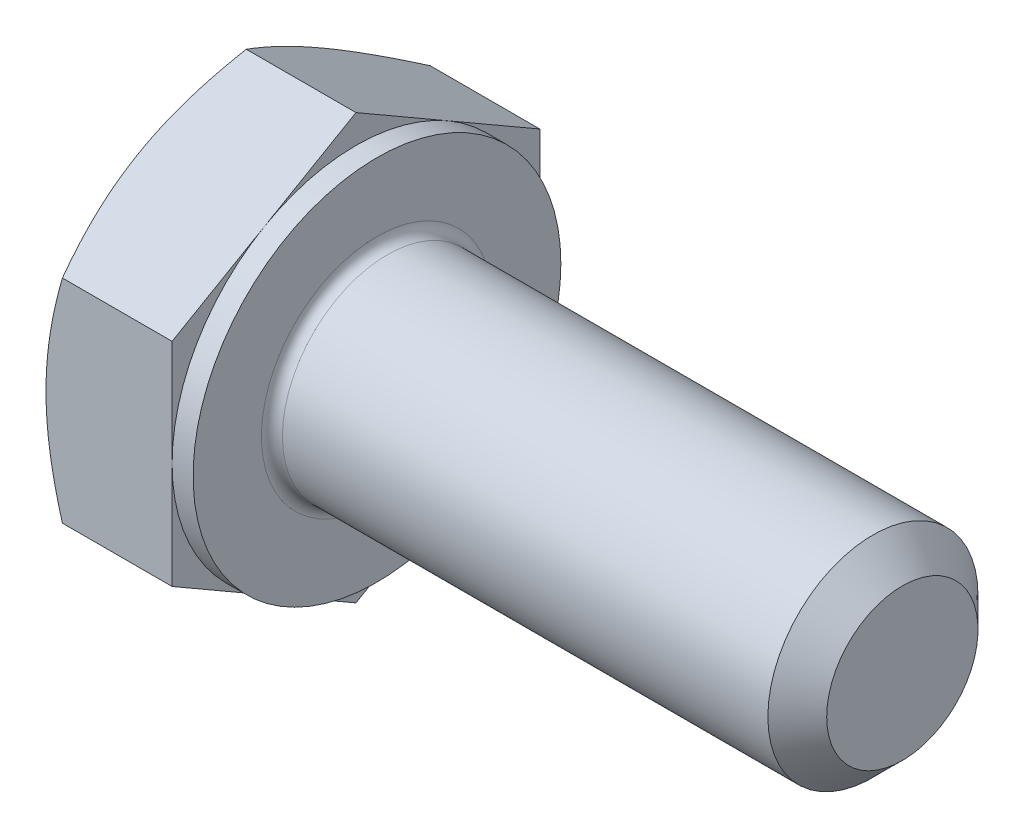
SolidWorks part; units mm, degrees
extrude "基体-拉伸" add sketch "草图1" along normal blind 2.8
sketch "草图1" plane through (0, 0, 0) normal (1, 0, 0) x (0, 0, -1)
  line L0 (3.5, 2.0207) -> (3.5, -2.0207)
  line L1 (-3.5, 2.0207) -> (-3.5, -2.0207)
  line L2 (3.5, -2.0207) -> (0, -4.0415)
  line L3 (0, -4.0415) -> (-3.5, -2.0207)
  line L4 (3.5, 2.0207) -> (0, 4.0415)
  line L5 (0, 4.0415) -> (-3.5, 2.0207)
  dimension "s" = 7
  dimension "D2" = 120
  dimension "D3" = 3.5
  dimension "D4" = 3.5
  dimension "D5" = 3.5
revolve "切除-旋转1" cut sketch "草图3" angle 360 about L6
sketch "草图3" plane through (0, 0, 0) normal (0, 0, 1) x (1, 0, 0)
  line L0 (0, 3.5) -> (3.1994, 9.0415)
  line L1 (0, 4.0415) -> (0, 2.0207) construction
  line L2 (3.1994, 9.0415) -> (3.1994, 14.0415)
  line L3 (3.1994, 14.0415) -> (-10, 14.0415)
  line L4 (-10, 14.0415) -> (-10, 3.5)
  line L5 (-10, 3.5) -> (0, 3.5)
  line L6 (0, 0) -> (99.06, 0) construction
  line L7 (2.8, 4.0415) -> (0, 4.0415) construction
  dimension "D1" = 3.5
  dimension "D2" = 5
  dimension "D3" = 10
  dimension "D4" = 5
  dimension "Head_ch_ang" = 30
revolve "凸台-旋转1" add sketch "草图2" angle 360 about L7
sketch "草图2" plane through (0, 0, 0) normal (0, 0, 1) x (1, 0, 0)
  line L0 (0, 2.0207) -> (0, -2.0207) construction
  line L1 (0, 0) -> (12.8, 0)
  line L2 (0, 0) -> (0, 2)
  line L3 (0, 2) -> (12.8, 2)
  line L4 (12.8, 0) -> (12.8, 1.3938)
  line L5 (2.8, 4.0415) -> (2.8, 2.0207) construction
  line L7 (0, 0) -> (96.52, 0) construction
  line L8 (12.8, -1.3938) -> (90.335, -2) construction
  line L9 (0, -2) -> (90.335, -2) construction
  line L10 (3.5, 15.24) -> (3.5, -1.27) construction
  line L11 (2.8, 15.24) -> (2.8, -1.27) construction
  line L12 (2.8, 2.0207) -> (2.8, -2.0207) construction
  line L14 (12.8, 2) -> (12.8, 1.3938)
  dimension "l" = 10
  dimension "m" = 4
  dimension "Minor_dia" = 2.7876
  dimension "p" = 0.7
  dimension "h" = 10
cosmetic thread "螺旋线1" parameters "Thread_length"=9.3, "Thread_minor"=2.7876
material "5.6级"
ref_plane "前视" through (0, 0, 0) normal (0, 0, 1) x (1, 0, 0)
ref_plane "上视" through (0, 0, 0) normal (0, 1, 0) x (1, 0, 0)
ref_plane "右视" through (0, 0, 0) normal (1, 0, 0) x (0, 0, -1)
sketch "草图5" plane through (0, 0, 0) normal (0, 0, 1) x (1, 0, 0)
  line L0 (2.8, 3.5) -> (-0.3994, 9.0415)
  line L1 (2.8, 4.0415) -> (2.8, 2.0207) construction
  line L2 (-0.3994, 9.0415) -> (-0.3994, 14.0415)
  line L3 (-0.3994, 14.0415) -> (9.6006, 14.0415)
  line L4 (9.6006, 14.0415) -> (9.6006, 3.5)
  line L5 (9.6006, 3.5) -> (2.8, 3.5)
  line L7 (2.8, 4.0415) -> (0.3126, 4.0415) construction
  line L8 (0, 0) -> (99.06, 0) construction
  line L9 (0, 0) -> (99.06, 0) construction
  dimension "D1" = 3.5
  dimension "D2" = 5
  dimension "D3" = 10
  dimension "D4" = 5
  dimension "Head_ch_ang" = 30
revolve "切除-旋转2" cut sketch "草图5" angle 360 about L8
sketch "草图4" plane through (0, 0, 0) normal (0, 0, 1) x (1, 0, 0)
  line L1 (2.8, 4.0415) -> (2.8, 2.0207) construction
  line L2 (2.8, 3.5) -> (2.4, 3.5)
  line L3 (2.8, 3.5) -> (2.8, 14.0415)
  line L4 (2.8, 14.0415) -> (2.4, 14.0415)
  line L5 (0, 0) -> (95.25, 0) construction
  line L6 (0, 0) -> (96.52, 0) construction
  line L7 (2.4, 3.5) -> (2.4, 14.0415)
  line L8 (2.4874, 4.0415) -> (0.3126, 4.0415) construction
  dimension "D2" = 10
  dimension "D1" = 7
revolve "切除-旋转3" cut sketch "草图4" angle 360 about L5
chamfer "倒角" distance 0.56 angle 45 1 edges at (12.8, 0, 2)
fillet "圆角" radius 0.2 1 edges at (2.8, 0, -2)
sketch "草图6" plane through (0, 0, 0) normal (0, 0, 1) x (1, 0, 0)
  line L0 (3.35, -1.3938) -> (3, -2)
  line L1 (3.35, -1.3938) -> (3.7, -2)
  line L2 (3.7, -2) -> (3.7, -2.5)
  line L3 (-3.175, 0) -> (5.1513, 0) construction
  line L5 (3.7, -2.5) -> (3, -2.5)
  line L6 (3, -2.5) -> (3, -2)
  arc A0 (3, -2) -> (2.8, -2.2) centre (3, -2.2) ccw construction
  dimension "Thread_minor" = 2.7876
  dimension "Diameter" = 4
revolve "切除-旋转4" [suppressed] cut sketch "草图6" angle 360 about L3
pattern_linear "阵列(线性)1" [suppressed]
equation "\"D3@草图1\" = \"s@草图1\" / 2"
equation "\"D4@草图1\" = \"D3@草图1\""
equation "\"D5@草图1\" = \"D4@草图1\""
equation "\"D1@草图3\" = \"s@草图1\" / 2"
equation "\"D1@草图5\" = \"s@草图1\" / 2"
equation "\"Head_ch_ang@草图5\" = \"Head_ch_ang@草图3\""
equation "\"D1@草图4\" = \"s@草图1\""
equation "\"Diameter@草图6\" = \"m@草图2\""
equation "\"Overcut@草图6\" = \"m@草图2\" * 1.25"
equation "\"Minor_dia@草图2\" = \"m@草图2\"-\"p@草图2\" * 1.732"
equation "\"Thread_minor@螺旋线1\" = \"Minor_dia@草图2\""
equation "\"Thread_minor@草图6\" = \"Minor_dia@草图2\""
equation "\"D1@倒角\" = \"p@草图2\"*0.8"
equation "\"Thread_length@螺旋线1\" = \"l@草图2\" - \"p@草图2\""
equation "\"Num_threads@阵列(线性)1\" = \"l@草图2\" / \"p@草图2\""
